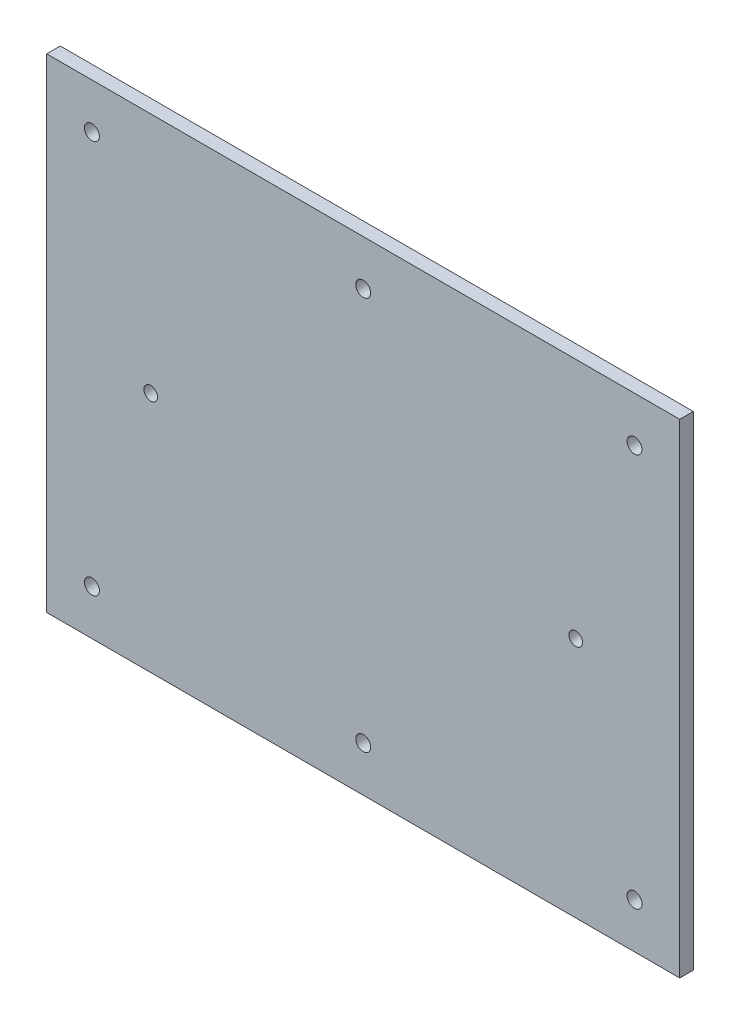
SolidWorks part; units mm, degrees
ref_plane "Plan de face" through (0, 0, 0) normal (0, 0, 1) x (1, 0, 0)
ref_plane "Plan de dessus" through (0, 0, 0) normal (0, 1, 0) x (1, 0, 0)
ref_plane "Plan de droite" through (0, 0, 0) normal (1, 0, 0) x (0, 0, -1)
sketch "Esquisse1" plane through (0, 0, 0) normal (0, 0, 1) x (1, 0, 0)
  line L0 (-20, 87) -> (0, 67) construction
  line L1 (0, 0) -> (100, 0) construction
  line L2 (0, 0) -> (0, 67) construction
  line L3 (0, 67) -> (100, 67) construction
  line L4 (100, 0) -> (100, 67) construction
  line L5 (-20, 87) -> (120, 87)
  line L6 (-20, 87) -> (-20, -20)
  line L7 (-20, -20) -> (120, -20)
  line L8 (120, 87) -> (120, -20)
  line L9 (100, 67) -> (120, 87) construction
  line L10 (100, 0) -> (120, -20) construction
  line L11 (0, 0) -> (-20, -20) construction
  line L12 (110, 77) -> (-10, 77) construction
  line L13 (-10, 77) -> (-10, -10) construction
  line L14 (-10, -10) -> (110, -10) construction
  line L15 (110, -10) -> (110, 77) construction
  line L16 (100, 33.5) -> (0, 33.5) construction
  line L17 (3, 51.1933) -> (3, 11.8866) construction
  line L18 (97, 11.8866) -> (97, 51.1933) construction
  circle A0 centre (97, 33.5) radius 1.5
  circle A1 centre (3, 33.5) radius 1.5
  circle A2 centre (110, 77) radius 1.65
  circle A3 centre (-10, 77) radius 1.65
  circle A4 centre (-10, -10) radius 1.65
  circle A5 centre (110, -10) radius 1.65
  circle A6 centre (50, 77) radius 1.65
  circle A7 centre (50, -10) radius 1.65
  point P9 (50, -20)
  dimension "D9" = 3
  dimension "D10" = 3
  dimension "D11" = 3.3
  dimension "D1" = 67
  dimension "D2" = 100
  dimension "D3" = 20
  dimension "D4" = 20
  dimension "D5" = 20
  dimension "D6" = 20
  dimension "D7" = 3
  dimension "D8" = 3
extrude "Boss.-Extru.1" add sketch "Esquisse1" along normal blind 3
